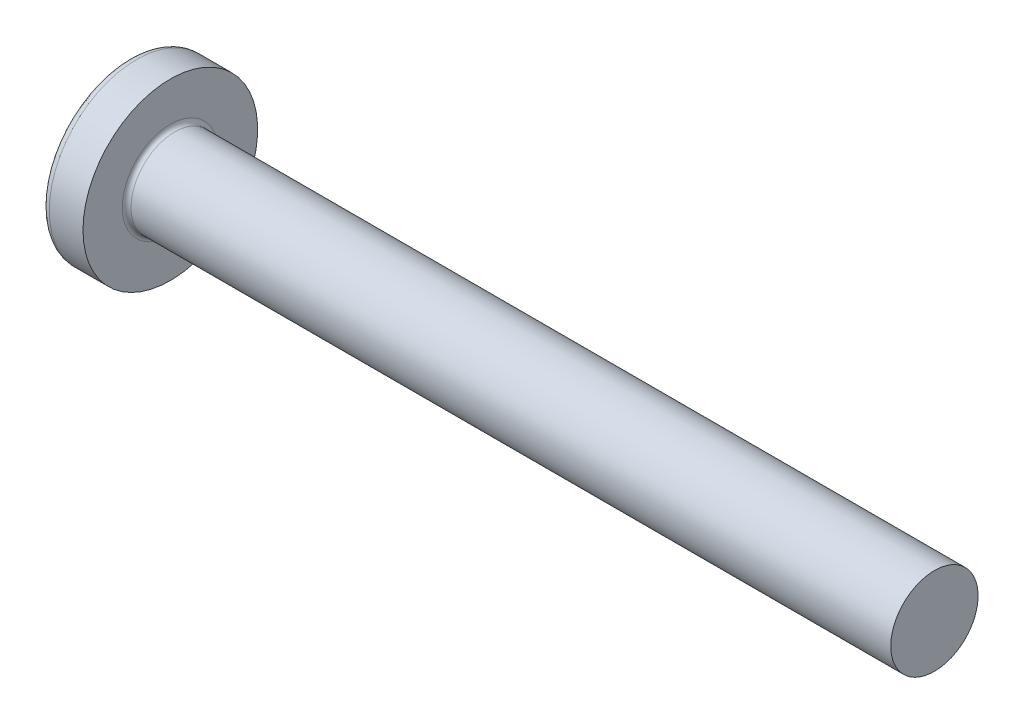
SolidWorks part; units mm, degrees
material "普通碳钢"
ref_plane "Plane1" through (0, 0, 0) normal (0, 0, 1) x (1, 0, 0)
ref_plane "Plane2" through (0, 0, 0) normal (0, 1, 0) x (1, 0, 0)
ref_plane "Plane3" through (0, 0, 0) normal (1, 0, 0) x (0, 0, -1)
sketch "BodySke" plane through (0, 0, 0) normal (0, 0, 1) x (1, 0, 0)
  line L0 (3.1, 2) -> (3.1, 4)
  line L1 (3.45, 6.35) -> (3.45, -3.175) construction
  line L2 (-25.4, 0) -> (127, 0) construction
  line L3 (38.1, 0) -> (0, 0)
  line L4 (3.1, 2) -> (38.1, 2)
  line L5 (38.1, 2) -> (38.1, 0)
  line L6 (1.5553, 4) -> (3.1, 4)
  line L8 (32.1, 6.35) -> (32.1, -3.175) construction
  arc A0 (1.2654, 3.8534) -> (0, 0) centre (6.5, 0) ccw
  arc A2 (1.2654, 3.8534) -> (1.5553, 4) centre (1.5553, 3.64) cw
  dimension "Head_crown_rad" = 6.5
  dimension "Head_fillet_rad" = 0.36
  dimension "Length" = 35
  dimension "Head_ht" = 3.1
  dimension "Head_dia" = 8
  dimension "Advance" = 0.7
  dimension "Thread_nom" = 6
  dimension "Diameter" = 4
revolve "Base-Revolve" add sketch "BodySke"
cosmetic thread "ThreadCosmetic" [suppressed]
fillet "Fillet1" radius 0.2 1 edges at (3.1, 0, 2)
sketch "Sketch3" plane through (0, 0, 0) normal (1, 0, 0) x (0, 0, -1)
  line L0 (0.515, -2.15) -> (-0.515, -2.15)
  line L1 (0.515, -2.15) -> (0.515, 2.15)
  line L2 (-0.515, 2.15) -> (0.515, 2.15)
  line L3 (-0.515, 2.15) -> (-0.515, -2.15)
  dimension "Cross_dia" = 4.3
  dimension "D1" = 2.15
  dimension "Cross_width" = 1.03
  dimension "D2" = 0.515
ref_plane "Plane4" through (2.34, 0, 0) normal (1, 0, 0) x (0, 0, -1)
sketch "Sketch4" plane through (2.34, 0, 0) normal (1, 0, 0) x (0, 0, -1)
  line L0 (0.515, -0.9833) -> (-0.515, -0.9833)
  line L1 (0.515, -0.9833) -> (0.515, 0.9833)
  line L2 (-0.515, 0.9833) -> (0.515, 0.9833)
  line L3 (-0.515, 0.9833) -> (-0.515, -0.9833)
  dimension "D1" = 1.03
  dimension "D2" = 1.9666
  dimension "D3" = 0.515
  dimension "D4" = 0.9833
loft "Recess" cut profiles "Sketch3", "Sketch4"
pattern_circular "RecPat" count 2 every 90 about axis through (0, 0, 0) along (1, 0, 0) of "Recess"
sketch "RecCorSke" plane through (0, 0, 0) normal (0, 0, 1) x (1, 0, 0)
  line L0 (-3.175, 0) -> (15.875, 0) construction
  line L1 (-25.4, 0) -> (127, 0) construction
  line L2 (0, 0) -> (0, 1.0146)
  line L3 (0, 1.0146) -> (2.34, 0.851)
  line L4 (2.34, 0.851) -> (2.6165, 0)
  line L5 (2.6165, 0) -> (0, 0)
  dimension "Diameter" = 1.702
  dimension "Depth" = 2.34
  dimension "Draft_angle" = 4
  dimension "Bottom_angle" = 18
revolve "RecessCore" cut sketch "RecCorSke" angle 360 about L0
sketch "ThdSchSke" plane through (0, 0, 0) normal (0, 0, 1) x (1, 0, 0)
  line L0 (27.1, -1.61) -> (26.8269, -2)
  line L1 (27.1, -1.61) -> (27.3731, -2)
  line L2 (27.3731, -2) -> (27.3731, -2.5)
  line L3 (-3.175, 0) -> (5.1513, 0) construction
  line L5 (27.3731, -2.5) -> (26.8269, -2.5)
  line L6 (26.8269, -2.5) -> (26.8269, -2)
  dimension "Diameter" = 4
  dimension "SideAngle" = 55
  dimension "VeeAngle" = 70
  dimension "Thread_minor" = 3.22
  dimension "Overcut" = 5
  dimension "Start" = 27.1
revolve "ThreadSchematic" [suppressed] cut sketch "ThdSchSke" angle 360 about L3
pattern_linear "ThdSchPat" [suppressed]
sketch "草图1" plane through (38.1, 0, 0) normal (1, 0, 0) x (0, 0, -1)
  circle A0 centre (0, 0) radius 2 construction
  circle A1 centre (0, 0) radius 2
equation "\"D1@Sketch3\" = \"Cross_dia@Sketch3\" / 2"
equation "\"D2@Sketch3\" = \"Cross_width@Sketch3\" / 2"
equation "\"Depth@RecCorSke\" = \"Cross_depth@Plane4\""
equation "\"D1@Sketch4\" = \"Cross_width@Sketch3\""
equation "\"D2@Sketch4\" = \"Cross_dia@Sketch3\" - 2.0 * \"Cross_depth@Plane4\" * tan(26.5  * 0.017453292)"
equation "\"D3@Sketch4\" = \"D1@Sketch4\" / 2"
equation "\"D4@Sketch4\" = \"D2@Sketch4\" / 2"
equation "\"Thread_length@ThreadCosmetic\" = ((sgn( (\"Length@BodySke\" - \"Advance@BodySke\" * 2.0 ) - \"Thread_nom@BodySke\" )-1)*( (\"Length@BodySke\" - \"Advance@BodySke\" * 2.0 ) - \"Thread_nom@BodySke\" ))/-2+ \"Thread_nom@BodySke\""
equation "\"Thread_minor@ThdSchSke\" = \"Thread_minor@ThreadCosmetic\""
equation "\"Diameter@ThdSchSke\" = \"Diameter@BodySke\""
equation "\"Overcut@ThdSchSke\" = \"Diameter@BodySke\" * 1.25"
equation "\"Start@ThdSchSke\" = \"Head_ht@BodySke\" + \"Length@BodySke\" - \"Thread_length@ThreadCosmetic\"  '---Non-countersunk---"
equation "\"Num_threads@ThdSchPat\" = int( \"Thread_length@ThreadCosmetic\" / \"Advance@BodySke\" + 0.999 )  + 1"
equation "\"Advance@ThdSchPat\" = \"Thread_length@ThreadCosmetic\" /  (\"Num_threads@ThdSchPat\" - 1) 'relax it"
